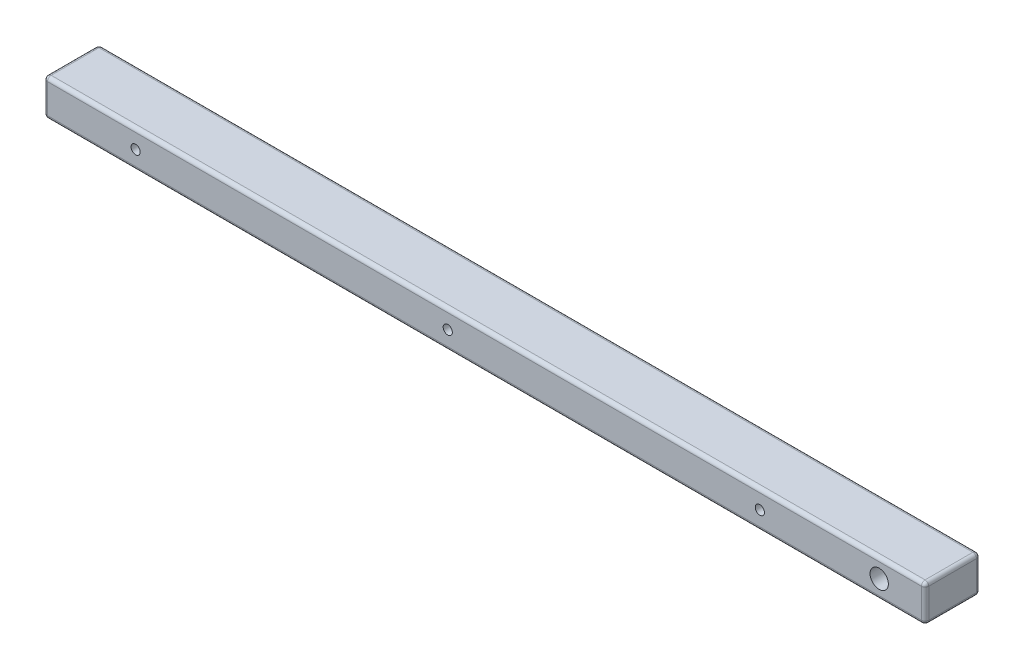
SolidWorks part; units mm, degrees
material "1023 Carbon Steel Sheet (SS)"
ref_plane "Ön Düzlem" through (0, 0, 0) normal (0, 0, 1) x (1, 0, 0)
ref_plane "Üst Düzlem" through (0, 0, 0) normal (0, 1, 0) x (1, 0, 0)
ref_plane "Sağ Düzlem" through (0, 0, 0) normal (1, 0, 0) x (0, 0, -1)
sketch "Sketch1" plane through (0, 0, 0) normal (0, 0, 1) x (1, 0, 0)
  line L0 (-240, 0) -> (240, 0)
  line L1 (240, 0) -> (240, 20)
  line L2 (240, 20) -> (-240, 20)
  line L3 (-240, 20) -> (-240, 0)
  dimension "D1" = 480
  dimension "D2" = 20
extrude "Boss-Extrude1" add sketch "Sketch1" along normal blind 30
fillet "Fillet1" radius 2 12 edges at (0, 0, 0) (240, 10, 0) (0, 20, 0) (-240, 10, 0) (-240, 10, 30) (-240, 0, 15) (-240, 20, 15) (240, 10, 30) (240, 0, 15) (240, 20, 15) (0, 0, 30) (0, 20, 30)
sketch "Sketch2" plane through (0, 0, 0) normal (0, 0, -1) x (-1, 0, 0)
  line L1 (-238, 20) -> (238, 20) construction
  line L2 (-240, 2) -> (-240, 18) construction
  circle A0 centre (-215, 10) radius 5
  dimension "D1" = 25
  dimension "D3" = 10
  dimension "D2" = 10
extrude "Cut-Extrude1" cut sketch "Sketch2" against normal blind 30
sketch "Sketch7" plane through (0, 0, 0) normal (0, 0, -1) x (-1, 0, 0)
  line L0 (-238, 20) -> (238, 20) construction
  circle A0 centre (-150, 10) radius 2.5
  circle A1 centre (20, 10) radius 2.5
  circle A2 centre (190, 10) radius 2.5
  dimension "D1" = 10
  dimension "D2" = 5
  dimension "D3" = 150
  dimension "D5" = 170
  dimension "D4" = 3
extrude "Cut-Extrude4" cut sketch "Sketch7" against normal up to surface (30 mm away) up to face at (210, 10, 30)
